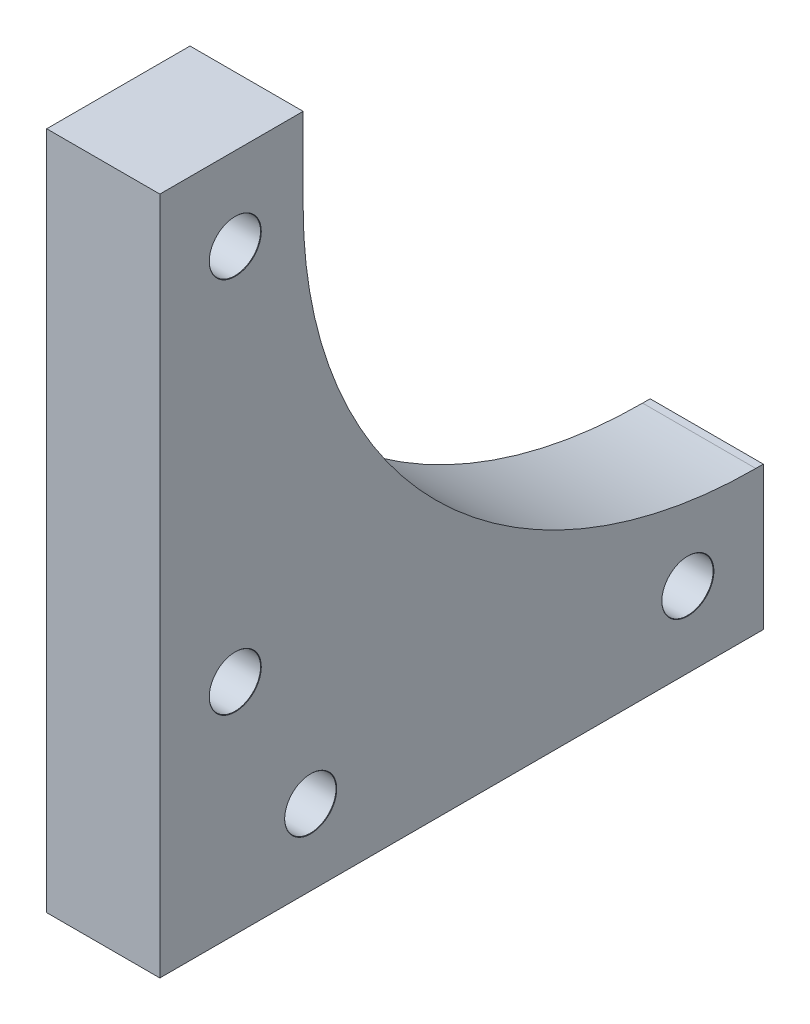
SolidWorks part; units mm, degrees
material "1060 Alloy"
ref_plane "Front Plane" through (0, 0, 0) normal (0, 0, 1) x (1, 0, 0)
ref_plane "Top Plane" through (0, 0, 0) normal (0, 1, 0) x (1, 0, 0)
ref_plane "Right Plane" through (0, 0, 0) normal (1, 0, 0) x (0, 0, -1)
sketch "Sketch1" plane through (0, 0, 0) normal (1, 0, 0) x (0, 0, -1)
  line L0 (0, 0) -> (0, 45)
  line L2 (40, 0) -> (0, 0)
  line L3 (0, 45) -> (9.5, 45)
  line L4 (9.5, 45) -> (9.5, 9.5)
  line L5 (9.5, 9.5) -> (40, 9.5)
  line L6 (40, 9.5) -> (40, 0)
  point P5 (40, 9.525)
  dimension "D1" = 40
  dimension "D2" = 9.5
  dimension "D3" = 45
extrude "Boss-Extrude1" add sketch "Sketch1" along normal blind 7.5
sketch "Sketch6" plane through (7.5, 0, 0) normal (1, 0, 0) x (0, 0, -1)
  line L0 (0, 45) -> (0, 0) construction
  line L1 (5, 39.5) -> (5, 14.5) construction
  line L2 (35, 5) -> (10, 5) construction
  line L3 (40, 9.5) -> (9.5, 9.5) construction
  line L5 (9.5, 9.5) -> (9.5, 45) construction
  point P11 (5, 39.5)
  point P12 (35, 5)
  point P13 (10, 5)
  dimension "D1" = 25
  dimension "D2" = 10
  dimension "D3" = 4.5
  dimension "D4" = 25
  dimension "D5" = 5
  dimension "D6" = 4.5
hole_wizard "M3 Clearance Hole1" positions "Sketch7" profile "Sketch9" hole size "M3" standard "ANSI Metric" end condition through all
sketch "Sketch7" plane through (7.5, 0, 0) normal (1, 0, 0) x (0, 0, -1)
  point P0 (35, 5)
  point P6 (10, 5)
  point P10 (5, 39.5)
  point P13 (5, 14.5)
sketch "Sketch9" plane through (7.5, 5, -35) normal (0, 1, 0) x (0, 0, -1)
  line L0 (0, 0) -> (0, 7.5)
  line L1 (0, 7.5) -> (1.7, 7.5)
  line L2 (1.7, 7.5) -> (1.7, 0.025)
  line L3 (1.7, 0.025) -> (1.725, 0)
  line L5 (1.725, 0) -> (0, 0)
  line L6 (-1.7, 0.025) -> (-1.725, 0) construction
  line L11 (0, -6.35) -> (0, 107.95) construction
  dimension "Thru Hole Dia." = 3.4
  dimension "Thru Hole Depth" = 7.5
  dimension "Near C'Sink Dia." = 3.45
  dimension "Near C'Sink Angle" = 90
fillet "Fillet1" radius 30 1 edges at (3.75, 9.5, -9.5)
